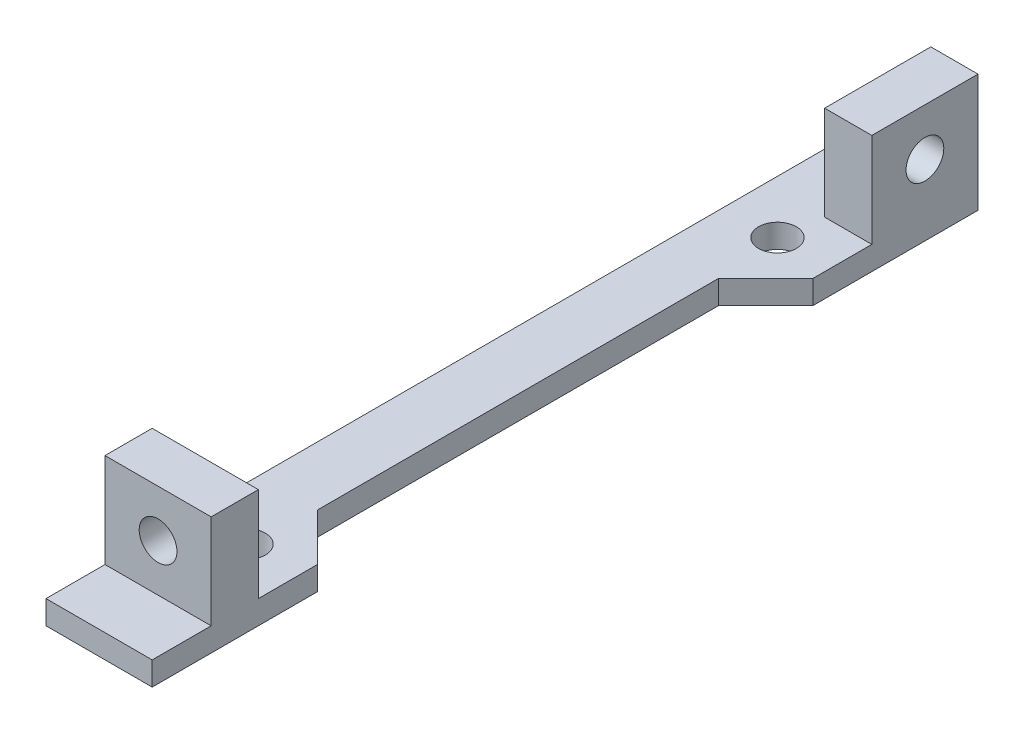
SolidWorks part; units mm, degrees
ref_plane "Plano frontal" through (0, 0, 0) normal (0, 0, 1) x (1, 0, 0)
ref_plane "Plano superior" through (0, 0, 0) normal (0, 1, 0) x (1, 0, 0)
ref_plane "Plano direito" through (0, 0, 0) normal (1, 0, 0) x (0, 0, -1)
sketch "Esboço6" plane through (0, 0, 0) normal (0, 1, 0) x (1, 0, 0)
  line L1 (-4.5, -35) -> (4.5, -35)
  line L2 (-4.5, -35) -> (-4.5, 35)
  line L3 (-4.5, 35) -> (4.5, 35)
  line L4 (4.5, -35) -> (4.5, 35)
  line L5 (-4.5, -35) -> (4.5, 35) construction
  line L6 (-4.5, 35) -> (4.5, -35) construction
  point P0 (0, 0)
  dimension "D1" = 70
  dimension "D2" = 9
extrude "Ressalto-extrusão5" add sketch "Esboço6" along normal blind 2
sketch "Esboço7" plane through (0, 2, 0) normal (0, 1, 0) x (1, 0, 0)
  line L0 (-4.5, 35) -> (-4.5, -35) construction
  line L1 (-4.5, -30) -> (4.5, -30)
  line L2 (-4.5, -30) -> (-4.5, -26)
  line L3 (-4.5, -26) -> (4.5, -26)
  line L4 (4.5, -30) -> (4.5, -26)
  line L5 (4.5, -35) -> (4.5, 35) construction
  line L6 (4.5, 35) -> (-4.5, 35) construction
  line L7 (0.5, 35) -> (4.5, 35)
  line L8 (0.5, 35) -> (0.5, 26)
  line L9 (0.5, 26) -> (4.5, 26)
  line L10 (4.5, 35) -> (4.5, 26)
  line L11 (-4.5, -35) -> (4.5, -35) construction
  dimension "D1" = 4
  dimension "D2" = 5
  dimension "D3" = 4
  dimension "D4" = 9
  dimension "D5" = 5
  dimension "D6" = 9
extrude "Ressalto-extrusão6" add sketch "Esboço7" along normal blind 8
sketch "Esboço8" plane through (0, 0, 30) normal (0, 0, 1) x (1, 0, 0)
  line L0 (0, 10) -> (0, 2) construction
  line L1 (-4.5, 10) -> (4.5, 10) construction
  line L2 (-4.5, 2) -> (4.5, 2) construction
  circle A0 centre (0, 6) radius 1.6
  point P8 (0, 6)
  dimension "D1" = 3.2
extrude "Corte-extrusão4" cut sketch "Esboço8" against normal blind 5
sketch "Esboço9" plane through (4.5, 0, 0) normal (1, 0, 0) x (0, 0, -1)
  line L0 (30.5, 10) -> (30.5, 2) construction
  line L1 (26, 10) -> (35, 10) construction
  circle A0 centre (30.5, 6) radius 1.6
  dimension "D1" = 3.2
extrude "Corte-extrusão5" cut sketch "Esboço9" against normal blind 5
sketch "Esboço10" plane through (0, 2, 0) normal (0, 1, 0) x (1, 0, 0)
  line L15 (0.5, 26) -> (0.5, -26) construction
  line L16 (4.5, -26) -> (-4.5, -26) construction
  line L21 (4.5, 21) -> (0.5, 17)
  line L22 (0.5, 17) -> (0.5, -17)
  line L23 (4.5, -26) -> (4.5, 26) construction
  line L24 (0.5, -17) -> (4.5, -21)
  line L25 (4.5, -21) -> (4.5, 21)
  dimension "D1" = 9
  dimension "D2" = 5
  dimension "D3" = 5
  dimension "D4" = 9
extrude "Corte-extrusão8" cut sketch "Esboço10" against normal through all
sketch "Esboço12" plane through (0, 2, 0) normal (0, 1, 0) x (1, 0, 0)
  line L0 (4.5, 22.5) -> (-4.5, 22.5) construction
  line L3 (4.5, 21) -> (4.5, 26) construction
  line L4 (-4.5, 35) -> (-4.5, -26) construction
  line L5 (0.5, 26) -> (4.5, 26) construction
  line L6 (4.5, -22.5) -> (-4.5, -22.5) construction
  line L7 (4.5, -26) -> (4.5, -21) construction
  line L8 (4.5, -26) -> (-4.5, -26) construction
  circle A1 centre (0, 22.5) radius 1.6
  circle A2 centre (0, -22.5) radius 1.6
  dimension "D1" = 3.2
  dimension "D3" = 3.2
  dimension "D2" = 3.5
  dimension "D4" = 3.5
extrude "Corte-extrusão9" cut sketch "Esboço12" against normal blind 5
